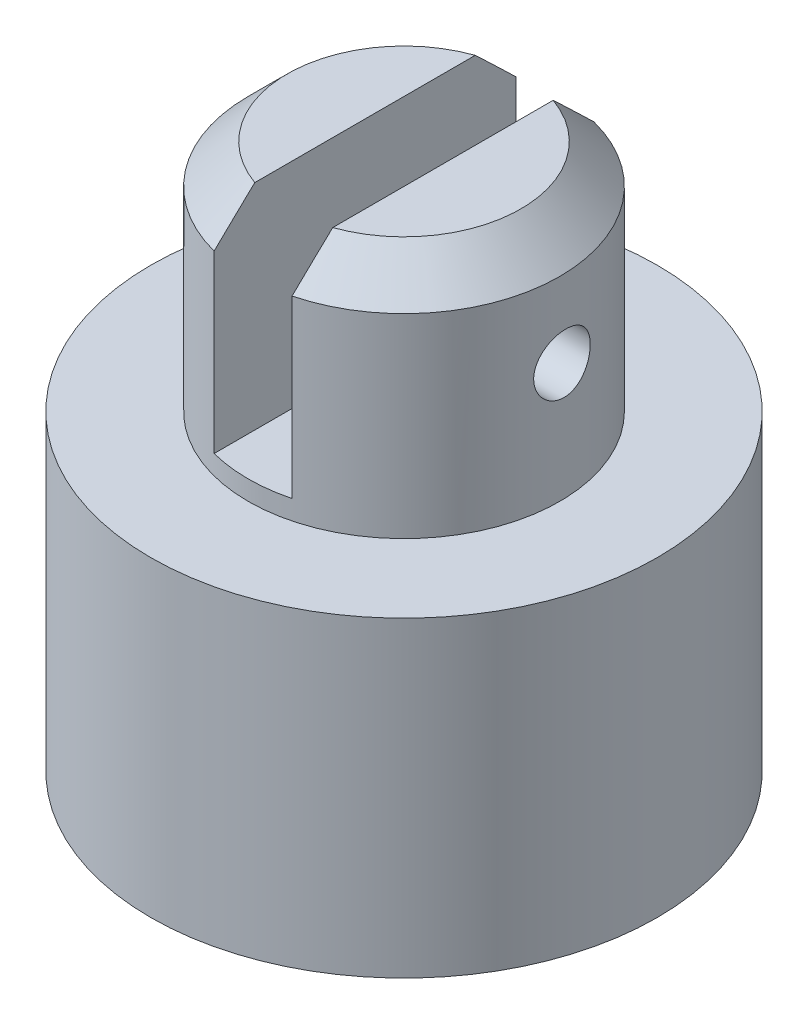
SolidWorks part; units mm, degrees
ref_plane "Front Plane" through (0, 0, 0) normal (0, 0, 1) x (1, 0, 0)
ref_plane "Top Plane" through (0, 0, 0) normal (0, 1, 0) x (1, 0, 0)
ref_plane "Right Plane" through (0, 0, 0) normal (1, 0, 0) x (0, 0, -1)
sketch "Sketch1" plane through (0, 0, 0) normal (0, 1, 0) x (1, 0, 0)
  circle A0 centre (0, 0) radius 6.5
  dimension "D1" = 13
extrude "Boss-Extrude1" add sketch "Sketch1" along normal blind 8
sketch "Sketch2" plane through (0, 8, 0) normal (0, 1, 0) x (1, 0, 0)
  circle A0 centre (0, 0) radius 4
  dimension "D1" = 8
extrude "Boss-Extrude2" add sketch "Sketch2" along normal blind 6
sketch "Sketch3" plane through (0, 14, 0) normal (0, 1, 0) x (1, 0, 0)
  line L1 (-1, -4.5) -> (1, -4.5)
  line L2 (-1, -4.5) -> (-1, 4.5)
  line L3 (-1, 4.5) -> (1, 4.5)
  line L4 (1, -4.5) -> (1, 4.5)
  line L5 (-1, -4.5) -> (1, 4.5) construction
  line L6 (-1, 4.5) -> (1, -4.5) construction
  point P0 (0, 0)
  dimension "D1" = 2
  dimension "D2" = 9
extrude "Cut-Extrude1" cut sketch "Sketch3" against normal blind 5.5
chamfer "Chamfer1" distance 1 angle 45 1 edges at (4, 14, 0)
chamfer "Chamfer2" distance 1 angle 45 1 edges at (-4, 14, 0)
sketch "Sketch5" plane through (0, 0, 0) normal (1, 0, 0) x (0, 0, -1)
  line L0 (2.8284, 14) -> (-2.8284, 14) construction
  line L1 (-3.873, 13) -> (-3.873, 8.5) construction
  circle A0 centre (0.127, 11.0027) radius 0.75
  point P4 (0, 14)
  dimension "D1" = 1.5
  dimension "D2" = 3
  dimension "D3" = 4
extrude "Cut-Extrude3" cut sketch "Sketch5" against normal blind 5.5 and the other way blind 5.5
